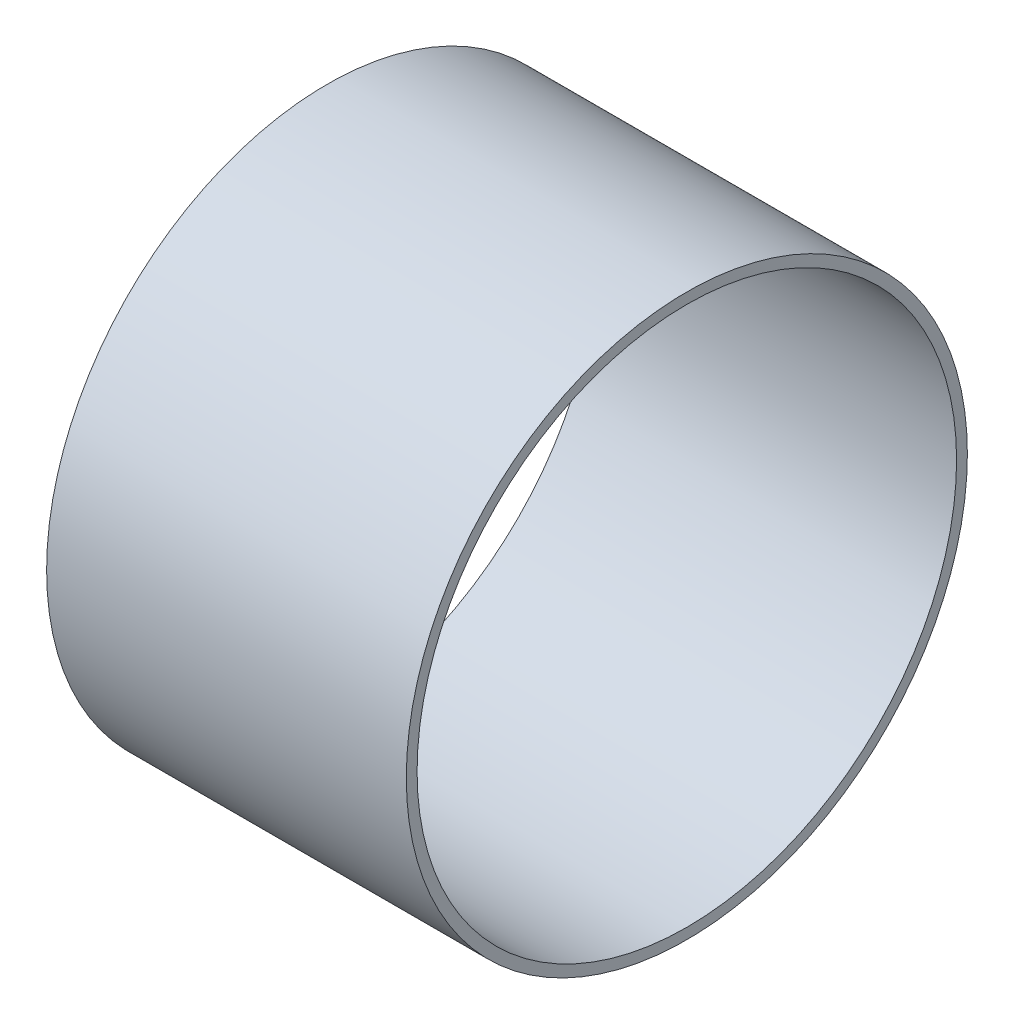
SolidWorks part; units mm, degrees
ref_plane "Front Plane" through (0, 0, 0) normal (1, 0, 0) x (0, 1, 0)
ref_plane "Top Plane" through (0, 0, 0) normal (0, 0, 1) x (0, 1, 0)
ref_plane "Right Plane" through (0, 0, 0) normal (0, 1, 0) x (-1, 0, 0)
sketch "Sketch1" plane through (0, 0, 0) normal (1, 0, 0) x (0, 1, 0)
  circle A0 centre (0, 0) radius 38.1
  circle A1 centre (0, 0) radius 39.624
  dimension "D1" = 79.248
  dimension "D2" = 76.2
extrude "Boss-Extrude1" add sketch "Sketch1" along normal blind 50.8
